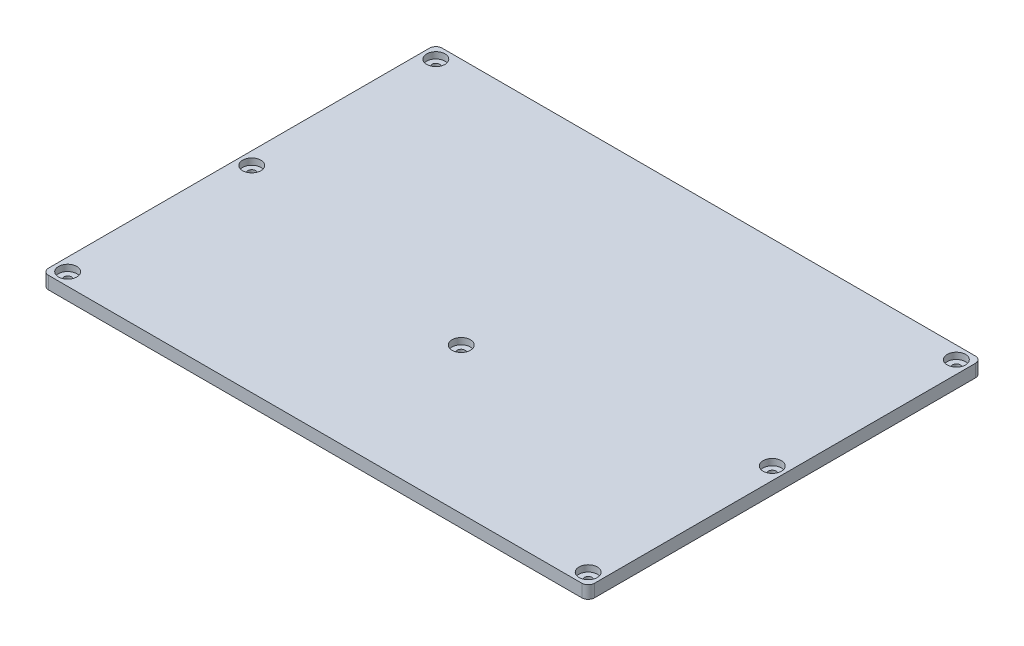
SolidWorks part; units mm, degrees
material "6061-T6 (SS)"
ref_plane "Front Plane" through (0, 0, 0) normal (0, 0, 1) x (1, 0, 0)
ref_plane "Top Plane" through (0, 0, 0) normal (0, 1, 0) x (1, 0, 0)
ref_plane "Right Plane" through (0, 0, 0) normal (1, 0, 0) x (0, 0, -1)
sketch "Sketch1" plane through (0, 0, 0) normal (0, 1, 0) x (1, 0, 0)
  line L1 (-136.525, 98.425) -> (136.525, 98.425)
  line L2 (-136.525, 98.425) -> (-136.525, -98.425)
  line L3 (-136.525, -98.425) -> (136.525, -98.425)
  line L4 (136.525, 98.425) -> (136.525, -98.425)
  line L5 (-136.525, 98.425) -> (136.525, -98.425) construction
  line L6 (-136.525, -98.425) -> (136.525, 98.425) construction
  point P0 (0, 0)
  dimension "D1" = 273.05
  dimension "D2" = 196.85
extrude "Boss-Extrude1" add sketch "Sketch1" along normal blind 6.35
hole_wizard "#6 Clearance Hole1" positions "Sketch2" profile "Sketch3" hole size "#6" standard "ANSI Inch" end condition through all
sketch "Sketch2" plane through (0, 6.35, 0) normal (0, 1, 0) x (1, 0, 0)
  line L0 (-130.175, 92.075) -> (130.175, -92.075)
  point P0 (-130.175, 92.075)
  point P2 (130.175, 92.075)
  point P4 (130.175, -92.075)
  point P6 (-130.175, -92.075)
  point P14 (-130.175, 0)
  point P16 (130.175, 0)
  point P24 (0, -25.4)
  point P27 (0, 0)
  dimension "D1" = 184.15
  dimension "D2" = 260.35
  dimension "D3" = 25.4
sketch "Sketch3" plane through (-130.175, 6.35, -92.075) normal (1, 0, 0) x (0, 0, 1)
  line L0 (0, 0) -> (0, 6.35)
  line L1 (0, 6.35) -> (1.8986, 6.35)
  line L2 (1.8986, 6.35) -> (1.8986, 0)
  line L5 (1.8986, 0) -> (0, 0)
  line L11 (0, -6.35) -> (0, 107.95) construction
  dimension "Thru Hole Dia." = 3.7973
  dimension "Thru Hole Depth" = 6.35
sketch "Sketch4" plane through (0, 6.35, 0) normal (0, 1, 0) x (1, 0, 0)
  line L1 (-127.8836, 88.1062) -> (-125.5923, 92.075) construction
  line L2 (-125.5923, 92.075) -> (-127.8836, 96.0437) construction
  line L3 (-127.8836, 96.0437) -> (-132.4664, 96.0437) construction
  line L4 (-132.4664, 96.0437) -> (-134.7577, 92.075) construction
  line L5 (-134.7577, 92.075) -> (-132.4664, 88.1062) construction
  line L6 (-132.4664, 88.1062) -> (-127.8836, 88.1062) construction
  circle A0 centre (-130.175, 92.075) radius 4.5827
  circle A1 centre (-130.175, 92.075) radius 3.9687 construction
  circle A2 centre (130.175, 92.075) radius 4.5827
  circle A3 centre (130.175, -92.075) radius 4.5827
  circle A4 centre (-130.175, -92.075) radius 4.5827
  circle A5 centre (-130.175, 0) radius 4.5827
  circle A6 centre (130.175, 0) radius 4.5827
  circle A7 centre (0, -25.4) radius 4.5827
  dimension "D1" = 7.9375
extrude "Cut-Extrude1" cut sketch "Sketch4" against normal blind 3.175
fillet "Fillet1" radius 3.175 4 edges at (136.525, 3.175, -98.425) (136.525, 3.175, 98.425) (-136.525, 3.175, 98.425) (-136.525, 3.175, -98.425)
